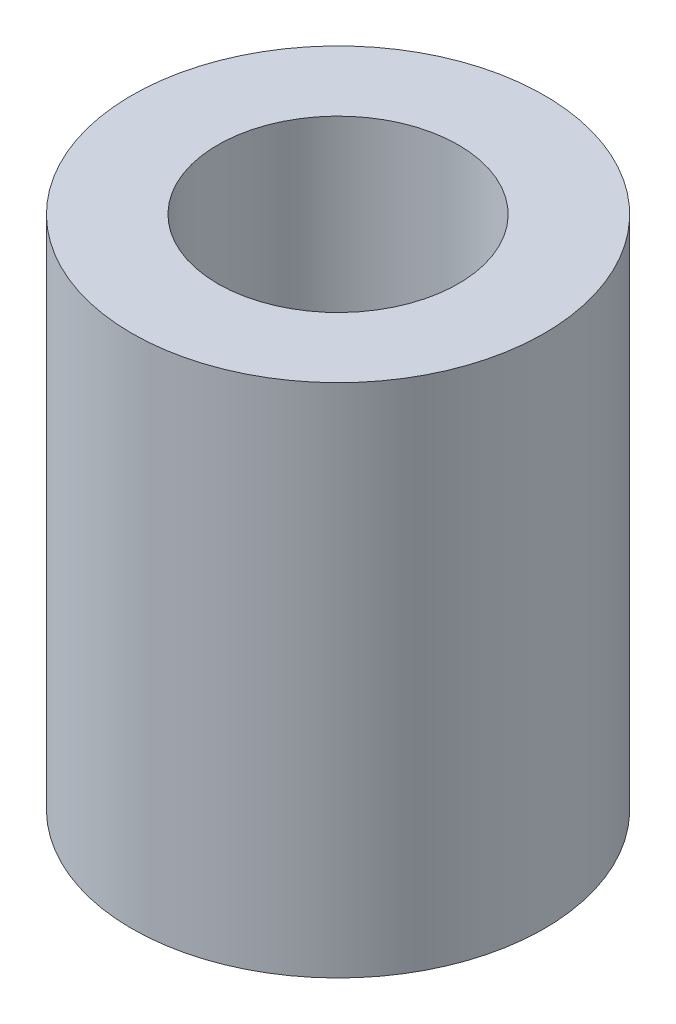
SolidWorks part; units mm, degrees
ref_plane "Front Plane" through (0, 0, 0) normal (0, 0, 1) x (1, 0, 0)
ref_plane "Top Plane" through (0, 0, 0) normal (0, 1, 0) x (1, 0, 0)
ref_plane "Right Plane" through (0, 0, 0) normal (1, 0, 0) x (0, 0, -1)
sketch "Sketch1" plane through (0, 0, 0) normal (0, 1, 0) x (1, 0, 0)
  circle A0 centre (0, 0) radius 6
  circle A1 centre (0, 0) radius 3.5
  dimension "D1" = 12
  dimension "D2" = 7
extrude "Boss-Extrude1" add sketch "Sketch1" along normal blind 15
cosmetic thread "Cosmetic Thread1"
